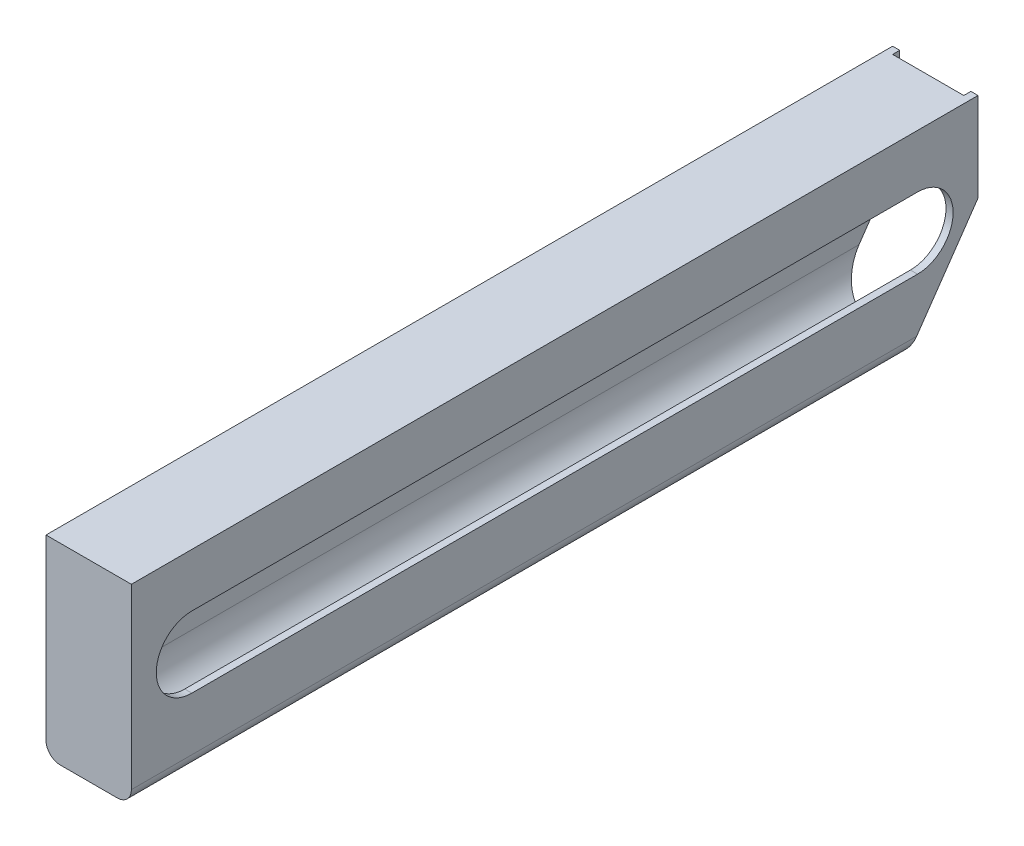
SolidWorks part; units mm, degrees
material "Cast Alloy Steel"
ref_plane "Front Plane" through (0, 0, 0) normal (0, 0, 1) x (1, 0, 0)
ref_plane "Top Plane" through (0, 0, 0) normal (0, 1, 0) x (1, 0, 0)
ref_plane "Right Plane" through (0, 0, 0) normal (1, 0, 0) x (0, 0, -1)
sketch "Sketch1" plane through (0, 0, 0) normal (0, 0, 1) x (1, 0, 0)
  line L0 (6, -12.5) -> (-6, 12.5) construction
  line L3 (-6, 12.5) -> (6, 12.5)
  line L5 (6, 12.5) -> (-6, -12.5) construction
  line L10 (-6, -12.5) -> (-6, 12.5)
  line L11 (6, 12.5) -> (6, -12.5)
  line L12 (4, -14.5) -> (-4, -14.5)
  line L13 (-983.3713, -12.5) -> (49016.6287, -12.5) construction
  line L14 (4, -1012.5) -> (4, 48987.5) construction
  line L15 (-4, -1012.5) -> (-4, 48987.5) construction
  arc A0 (6, -12.5) -> (4, -14.5) centre (4, -12.5) cw
  arc A2 (-4, -14.5) -> (-6, -12.5) centre (-4, -12.5) cw
  point P0 (0, 0)
  point P4 (0, 0)
  dimension "D3" = 8
  dimension "D1" = 12
  dimension "D4" = 27
  dimension "D6" = 2
extrude "Boss-Extrude1" add sketch "Sketch1" along normal blind 119
sketch "Sketch2" plane through (0, 0, 0) normal (0, 0, -1) x (-1, 0, 0)
  line L0 (-5, 11.5) -> (5, -8.3) construction
  line L2 (-5, -8.3) -> (-5, 11.5)
  line L3 (-5, 11.5) -> (5, 11.5)
  line L4 (5, -8.3) -> (5, 11.5)
  line L5 (5, 11.5) -> (-5, -8.3) construction
  line L6 (0, -1000) -> (0, 49000) construction
  line L7 (-6, 12.5) -> (6, 12.5) construction
  arc A0 (-5, -8.3) -> (5, -8.3) centre (0, -8.3) ccw
  point P0 (0, 0)
  point P8 (0, -13.3)
  point P10 (0, 1.6)
  dimension "D1" = 10
  dimension "D2" = 24.8
  dimension "D3" = 1
extrude "Cut-Extrude1" cut sketch "Sketch2" against normal blind 117
sketch "Sketch3" plane through (6, 0, 0) normal (1, 0, 0) x (0, 0, -1)
  line L0 (-1173, 0) -> (48827, 0) construction
  line L1 (-119, -12.5) -> (-119, 12.5) construction
  line L2 (-59.5, -979.25) -> (-59.5, 49020.75) construction
  line L3 (-119, 12.5) -> (0, 12.5) construction
  line L5 (-8.5, -5) -> (-110.5, -5)
  line L7 (-8.5, 5) -> (-110.5, 5)
  line L9 (-8.5, -5) -> (-110.5, 5) construction
  line L10 (-8.5, 5) -> (-110.5, -5) construction
  arc A0 (-110.5, 5) -> (-110.5, -5) centre (-110.5, 0) ccw
  arc A1 (-8.5, -5) -> (-8.5, 5) centre (-8.5, 0) ccw
  point P5 (-119, 0)
  point P6 (-59.5, 0)
  point P10 (-59.5, 12.5)
  dimension "D1" = 102
  dimension "D2" = 10
extrude "Cut-Extrude2" cut sketch "Sketch3" against normal through all
sketch "Sketch5" plane through (0, 12.5, 0) normal (0, 1, 0) x (1, 0, 0)
  line L1 (-5, 1) -> (5, 1)
  line L2 (-5, 1) -> (-5, -1)
  line L3 (-5, -1) -> (5, -1)
  line L4 (5, 1) -> (5, -1)
  line L5 (-5, 1) -> (5, -1) construction
  line L6 (-5, -1) -> (5, 1) construction
  point P0 (0, 0)
  dimension "D1" = 1
  dimension "D2" = 1
extrude "Cut-Extrude4" cut sketch "Sketch5" against normal through all
sketch "Sketch6" plane through (0, 0, 0) normal (1, 0, 0) x (0, 0, -1)
  line L0 (0, 0) -> (-10, -14.5)
  line L1 (-119, -14.5) -> (-1, -14.5) construction
  line L2 (-10, -14.5) -> (0, -14.5)
  line L3 (0, -14.5) -> (0, 0)
  dimension "D1" = 10
extrude "Cut-Extrude5" cut sketch "Sketch6" against normal through all and the other way through all
sketch "Sketch7" plane through (0, 0, 117) normal (0, 0, -1) x (-1, 0, 0)
  line L0 (0, -1000) -> (0, 994.3481) construction
  line L1 (-996.9774, -11) -> (49003.0226, -11) construction
  line L3 (-3, -9.75) -> (3, -9.75)
  line L4 (-3, -9.75) -> (-3, -12.25)
  line L5 (-3, -12.25) -> (3, -12.25)
  line L6 (3, -9.75) -> (3, -12.25)
  line L7 (-3, -9.75) -> (3, -12.25) construction
  line L8 (-3, -12.25) -> (3, -9.75) construction
  point P1 (0, -11)
  dimension "D1" = 11
  dimension "D2" = 2.5
  dimension "D3" = 6
extrude "Boss-Extrude2" add sketch "Sketch7" along normal blind 2.5
sketch "Sketch10" plane through (-3, 0, 0) normal (-1, 0, 0) x (0, 0, 1)
  line L0 (114.5, -12.25) -> (117, -9.75) construction
  line L1 (114.5, -9.75) -> (117, -9.75) construction
  line L2 (114.5, -9.75) -> (117, -12.25) construction
  line L3 (114.5, -12.25) -> (117, -12.25) construction
  circle A0 centre (115.75, -11) radius 1
  dimension "D1" = 2
extrude "Cut-Extrude6" cut sketch "Sketch10" against normal blind 6
